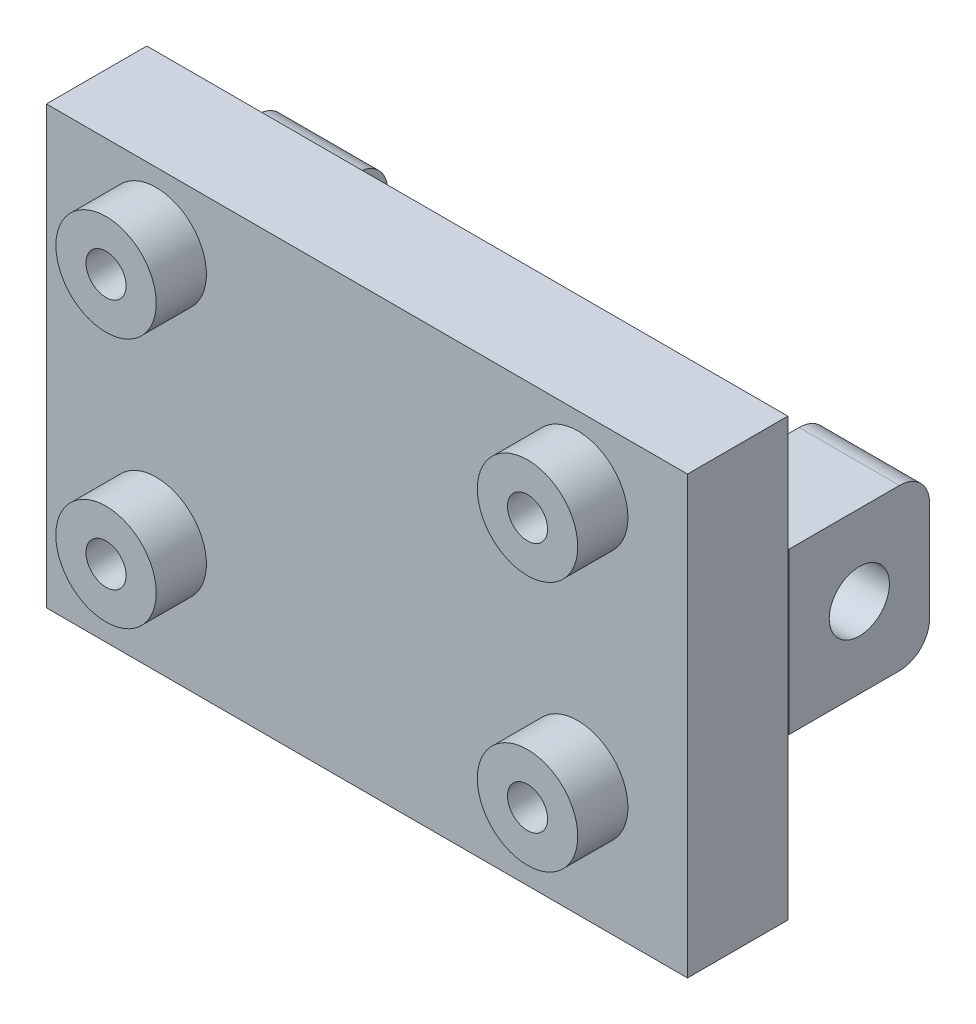
SolidWorks part; units mm, degrees
ref_plane "Plan de face" through (0, 0, 0) normal (0, 0, 1) x (1, 0, 0)
ref_plane "Plan de dessus" through (0, 0, 0) normal (0, 1, 0) x (1, 0, 0)
ref_plane "Plan de droite" through (0, 0, 0) normal (1, 0, 0) x (0, 0, -1)
sketch "Esquisse1" plane through (0, 0, 0) normal (0, 0, 1) x (1, 0, 0)
  line L0 (0, 0) -> (0, 11.4478) construction
  line L1 (-10.5, -6.25) -> (10.5, -6.25) construction
  line L2 (-10.5, -6.25) -> (-10.5, 6.25) construction
  line L3 (-10.5, 6.25) -> (10.5, 6.25) construction
  line L4 (10.5, -6.25) -> (10.5, 6.25) construction
  line L5 (-10.5, -6.25) -> (10.5, 6.25) construction
  line L6 (-10.5, 6.25) -> (10.5, -6.25) construction
  line L13 (-15.9697, -12.1254) -> (15.9697, -12.1254)
  line L14 (-15.9697, -12.1254) -> (-15.9697, 9.6188)
  line L15 (-15.9697, 9.6188) -> (15.9697, 9.6188)
  line L16 (15.9697, -12.1254) -> (15.9697, 9.6188)
  line L17 (-15.9697, -12.1254) -> (15.9697, 9.6188) construction
  line L18 (-15.9697, 9.6188) -> (15.9697, -12.1254) construction
  circle A0 centre (10.5, 6.25) radius 1
  circle A1 centre (10.5, -6.25) radius 1
  circle A2 centre (-10.5, -6.25) radius 1
  circle A3 centre (-10.5, 6.25) radius 1
  point P0 (0, 0)
  point P10 (0, -1.2533)
  point P11 (0, 0)
  point P14 (0, -1.2533)
  dimension "D3" = 2
  dimension "D4" = 2
  dimension "D5" = 2
  dimension "D6" = 2
  dimension "D1" = 21
  dimension "D2" = 12.5
extrude "Boss.-Extru.1" add sketch "Esquisse1" along normal blind 5
sketch "Esquisse2" plane through (0, 0, 5) normal (0, 0, 1) x (1, 0, 0)
  circle A0 centre (-10.5, 6.25) radius 2.5
  circle A1 centre (10.5, 6.25) radius 2.5
  circle A2 centre (10.5, -6.25) radius 2.5
  circle A3 centre (-10.5, -6.25) radius 2.5
  circle A4 centre (-10.5, 6.25) radius 1
  circle A6 centre (10.5, 6.25) radius 1
  circle A7 centre (10.5, -6.25) radius 1
  circle A8 centre (-10.5, -6.25) radius 1
  circle M6 centre (10.5, 6.25) radius 1
  circle M7 centre (10.5, -6.25) radius 1
  circle M8 centre (-10.5, -6.25) radius 1
  dimension "D1" = 5
  dimension "D2" = 5
  dimension "D3" = 5
  dimension "D4" = 5
extrude "Boss.-Extru.2" add sketch "Esquisse2" along normal blind 2.5 contours A3 M8 | A2 M7 | A1 M6 | A0 | A4
sketch "Esquisse4" plane through (-15.9697, 0, 0) normal (-1, 0, 0) x (0, 0, 1)
  line L0 (0, -4.0913) -> (-5.5, -4.0913)
  line L1 (0, 9.6188) -> (0, -12.1254) construction
  line L2 (-7, -2.5913) -> (-7, 2.4087)
  line L3 (-5.5, 3.9087) -> (0, 3.9087)
  line L4 (0, -4.0913) -> (0, 3.9087)
  line L5 (-7, -0.0913) -> (0, -0.0913) construction
  circle A0 centre (-3.5, -0.0913) radius 1.5
  arc A1 (-5.5, -4.0913) -> (-7, -2.5913) centre (-5.5, -2.5913) cw
  arc A2 (-7, 2.4087) -> (-5.5, 3.9087) centre (-5.5, 2.4087) cw
  point P12 (-7, -4.0913)
  point P15 (-7, 3.9087)
  dimension "D1" = 3
  dimension "D4" = 1.5
  dimension "D2" = 8
  dimension "D3" = 7
extrude "Boss.-Extru.3" add sketch "Esquisse4" against normal blind 5
pattern_linear "Répétition linéaire1" count 2 spacing 27 along (1, 0, 0) of "Boss.-Extru.3"
